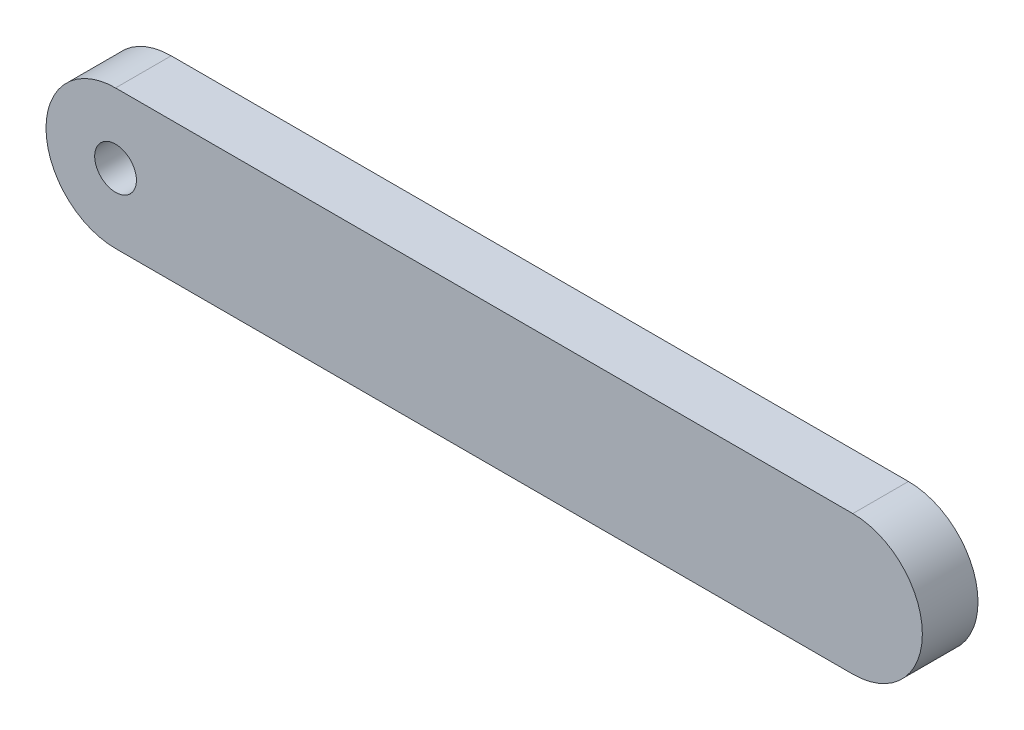
SolidWorks part; units mm, degrees
ref_plane "Front Plane" through (0, 0, 0) normal (0, 0, 1) x (1, 0, 0)
ref_plane "Top Plane" through (0, 0, 0) normal (0, 1, 0) x (1, 0, 0)
ref_plane "Right Plane" through (0, 0, 0) normal (1, 0, 0) x (0, 0, -1)
sketch "Sketch1" plane through (0, 0, 0) normal (0, 0, 1) x (1, 0, 0)
  line L0 (0, 0) -> (53, 0) construction
  line L1 (0, 5) -> (53, 5)
  line L2 (0, -5) -> (53, -5)
  arc A0 (0, 5) -> (0, -5) centre (0, 0) ccw
  arc A1 (53, -5) -> (53, 5) centre (53, 0) ccw
  circle A2 centre (0, 0) radius 1.5
  point P3 (26.5, 0)
  dimension "D2" = 5
  dimension "D3" = 3
  dimension "D1" = 53
extrude "Boss-Extrude1" add sketch "Sketch1" along normal blind 4
